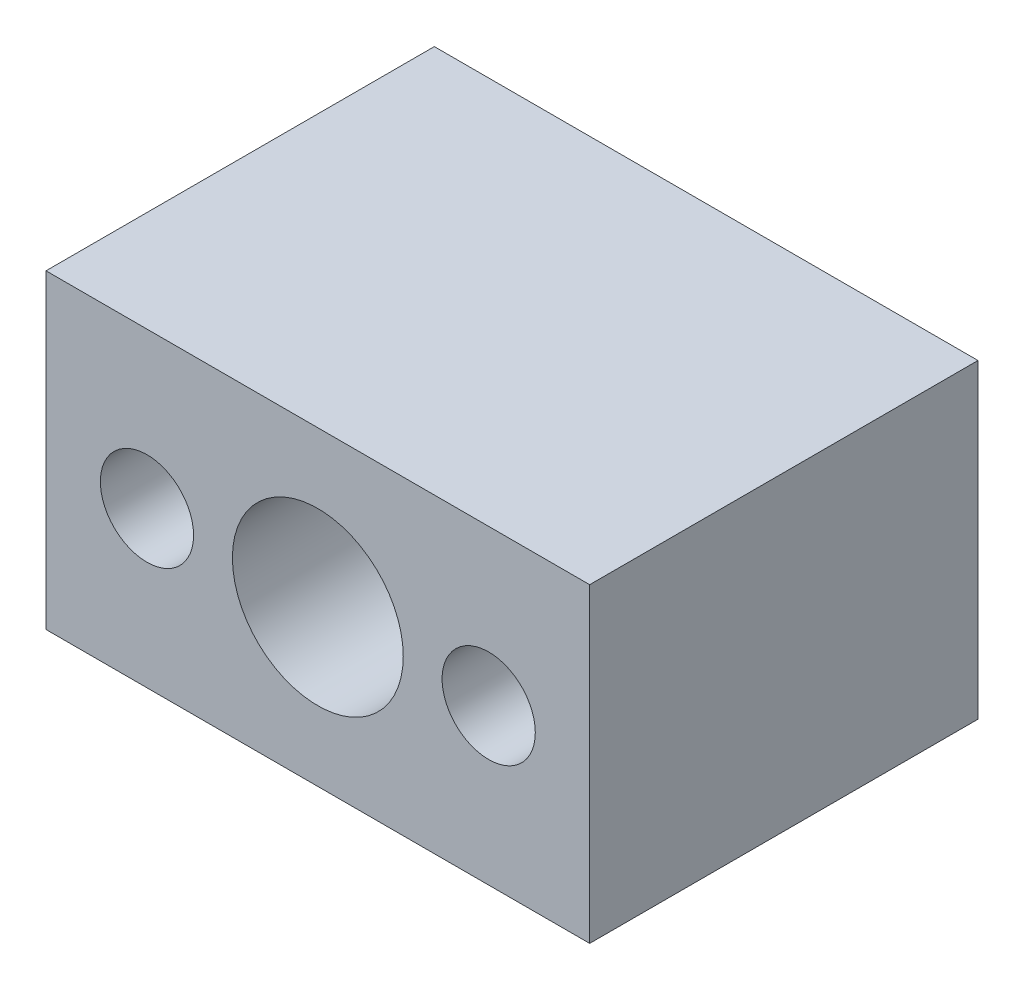
SolidWorks part; units mm, degrees
ref_plane "Front Plane" through (0, 0, 0) normal (0, 0, 1) x (1, 0, 0)
ref_plane "Top Plane" through (0, 0, 0) normal (0, 1, 0) x (1, 0, 0)
ref_plane "Right Plane" through (0, 0, 0) normal (1, 0, 0) x (0, 0, -1)
sketch "Sketch1" plane through (0, 0, 0) normal (0, 0, 1) x (1, 0, 0)
  line L1 (-35, 20) -> (35, 20)
  line L2 (-35, 20) -> (-35, -20)
  line L3 (-35, -20) -> (35, -20)
  line L4 (35, 20) -> (35, -20)
  line L5 (-35, 20) -> (35, -20) construction
  line L6 (-35, -20) -> (35, 20) construction
  point P0 (0, 0)
  dimension "D1" = 70
  dimension "D2" = 40
extrude "Boss-Extrude1" add sketch "Sketch1" along normal blind 50
sketch "Sketch2" plane through (0, 0, 50) normal (0, 0, 1) x (1, 0, 0)
  line L0 (0, 20) -> (0, -20) construction
  line L1 (35, 20) -> (-35, 20) construction
  line L2 (-35, -20) -> (35, -20) construction
  line L3 (-35, 0) -> (35, 0) construction
  line L4 (-35, 20) -> (-35, -20) construction
  line L5 (35, -20) -> (35, 20) construction
  circle A0 centre (0, 0) radius 11
  dimension "D1" = 22
extrude "Cut-Extrude1" cut sketch "Sketch2" against normal through all
sketch "Sketch3" plane through (0, 0, 50) normal (0, 0, 1) x (1, 0, 0)
  line L0 (0, 20) -> (0, -20) construction
  line L1 (35, 20) -> (-35, 20) construction
  line L2 (-35, -20) -> (35, -20) construction
  line L3 (-35, 0) -> (0, 0) construction
  line L4 (-35, 20) -> (-35, -20) construction
  line L5 (0, 0) -> (35, 0) construction
  line L6 (35, -20) -> (35, 20) construction
  circle A0 centre (-22, 0) radius 6
  circle A1 centre (22, 0) radius 6
  dimension "D2" = 12
  dimension "D1" = 22
  dimension "D3" = 22
extrude "Cut-Extrude2" cut sketch "Sketch3" against normal through all
